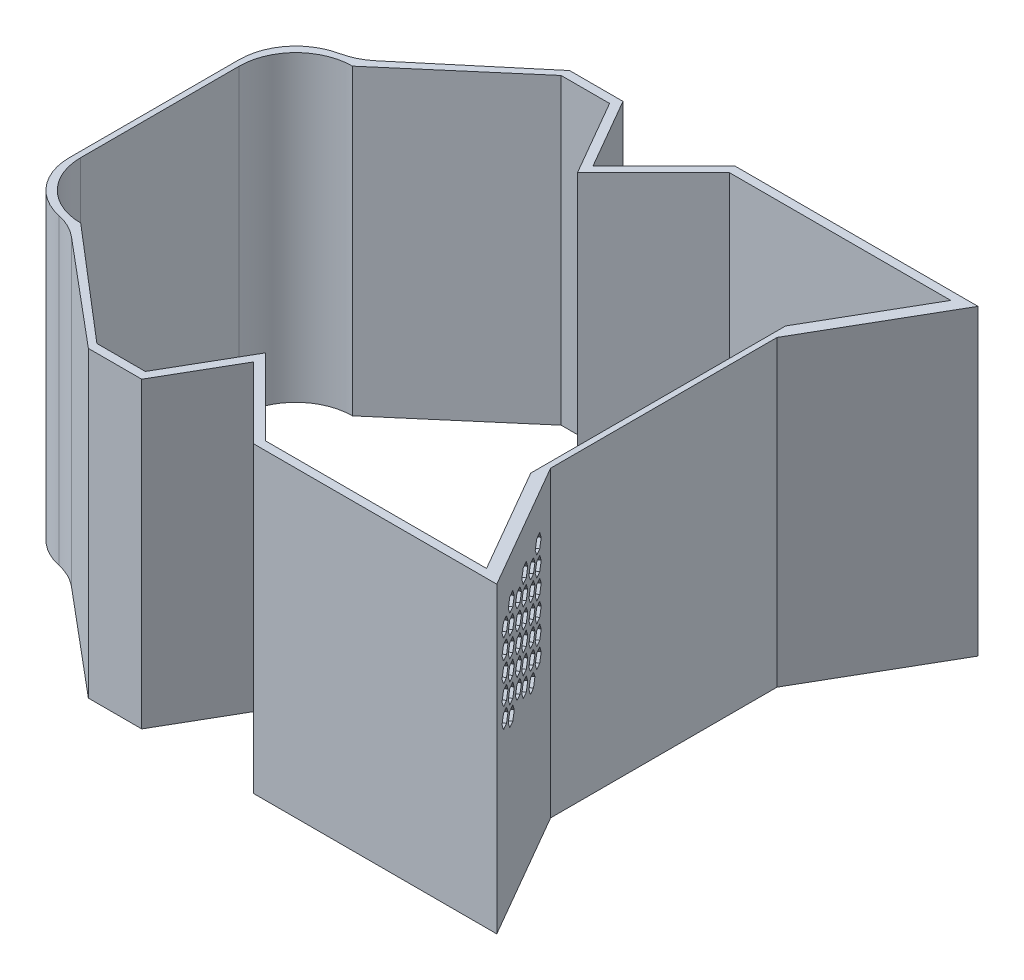
SolidWorks part; units mm, degrees
ref_plane "Ön Düzlem" through (0, 0, 0) normal (0, 0, 1) x (1, 0, 0)
ref_plane "Üst Düzlem" through (0, 0, 0) normal (0, 1, 0) x (1, 0, 0)
ref_plane "Sağ Düzlem" through (0, 0, 0) normal (1, 0, 0) x (0, 0, -1)
sketch "Çizim1" plane through (0, 0, 0) normal (0, 1, 0) x (1, 0, 0)
  line L2 (-90, -30) -> (-90, 30)
  line L4 (90, -40) -> (90, 40)
  line L6 (19.6213, -70.3787) -> (4.3568, -55.1141)
  line L8 (88, 0) -> (88, -38)
  line L9 (88, 38) -> (88, 0)
  line L14 (-88, 28) -> (-88, -28)
  line L22 (19.6213, -70.3787) -> (31.2426, -82)
  line L23 (5, -60) -> (30, -85)
  line L24 (-4.815, -71) -> (4.3568, -55.1141)
  line L25 (-28.2886, -85) -> (-9.4338, -85)
  line L26 (-65.4669, -53.8037) -> (-28.2886, -85)
  line L27 (5, -60) -> (-9.4338, -85)
  line L28 (30, -85) -> (115.9808, -85)
  line L29 (31.2426, -82) -> (109.362, -82)
  line L30 (90, -40) -> (115.9808, -85)
  line L31 (88, 45) -> (109.362, 82)
  line L32 (-68, -48) -> (-28.2886, -82)
  line L33 (-28.2886, -82) -> (-11.1658, -82)
  line L34 (-4.815, -71) -> (-11.1658, -82)
  line L35 (88, -38) -> (88, -45)
  line L36 (88, -45) -> (109.362, -82)
  line L37 (88, 38) -> (88, 45)
  line L38 (-4.815, 71) -> (-11.1658, 82)
  line L39 (-28.2886, 82) -> (-11.1658, 82)
  line L40 (-68, 48) -> (-28.2886, 82)
  line L41 (90, 40) -> (115.9808, 85)
  line L42 (31.2426, 82) -> (109.362, 82)
  line L43 (30, 85) -> (115.9808, 85)
  line L44 (5, 60) -> (-9.4338, 85)
  line L45 (-65.4669, 53.8037) -> (-28.2886, 85)
  line L46 (-28.2886, 85) -> (-9.4338, 85)
  line L47 (-4.815, 71) -> (4.3568, 55.1141)
  line L48 (5, 60) -> (30, 85)
  line L49 (19.6213, 70.3787) -> (31.2426, 82)
  line L50 (19.6213, 70.3787) -> (4.3568, 55.1141)
  arc A0 (-88, -28) -> (-68, -48) centre (-68, -28) ccw
  arc A2 (-74.1613, -49.5623) -> (-90, -30) centre (-70, -30) cw
  arc A8 (-65.4669, -53.8037) -> (-74.1613, -49.5623) centre (-78.3227, -69.1246) ccw
  arc A9 (-65.4669, 53.8037) -> (-74.1613, 49.5623) centre (-78.3227, 69.1246) cw
  arc A10 (-74.1613, 49.5623) -> (-90, 30) centre (-70, 30) ccw
  arc A11 (-88, 28) -> (-68, 48) centre (-68, 28) cw
  point P0 (0, 0)
  dimension "D1" = 20
extrude "Yükseklik-Ekstrüzyon1" add sketch "Çizim1" along normal blind 107
sketch "Çizim2" plane through (50.1795, 0, -28.9711) normal (0.866, 0, -0.5) x (-0.5, 0, -0.866)
  line L0 (-131.6025, 107) -> (-121.6025, 107)
  line L1 (-131.6025, 107) -> (-79.641, 107) construction
  line L2 (-121.6025, 107) -> (-111.6025, 107)
  line L3 (-111.6025, 107) -> (-101.6025, 107)
  line L4 (-101.6025, 107) -> (-91.6025, 107)
  line L5 (-91.6025, 107) -> (-81.6025, 107)
  line L7 (-90.1592, 80.5) -> (-88.7158, 78)
  line L10 (-90.1592, 24.5) -> (-88.7158, 22)
  line L13 (-88.7158, 36) -> (-90.1592, 38.5)
  line L15 (-88.7158, 92) -> (-90.1592, 94.5)
  line L16 (-90.1592, 94.5) -> (-93.0459, 94.5)
  line L17 (-93.0459, 94.5) -> (-94.4893, 92)
  line L18 (-94.4893, 92) -> (-93.0459, 89.5)
  line L19 (-93.0459, 89.5) -> (-90.1592, 89.5)
  line L20 (-90.1592, 89.5) -> (-88.7158, 92)
  line L30 (-88.7158, 85) -> (-90.1592, 87.5)
  line L31 (-90.1592, 87.5) -> (-93.0459, 87.5)
  line L32 (-93.0459, 87.5) -> (-94.4893, 85)
  line L33 (-94.4893, 85) -> (-93.0459, 82.5)
  line L34 (-93.0459, 82.5) -> (-90.1592, 82.5)
  line L35 (-90.1592, 82.5) -> (-88.7158, 85)
  line L36 (-103.1592, 80.5) -> (-101.7158, 78)
  line L37 (-103.1592, 24.5) -> (-101.7158, 22)
  line L38 (-93.0459, 80.5) -> (-90.1592, 80.5)
  line L39 (-94.4893, 78) -> (-93.0459, 80.5)
  line L40 (-93.0459, 75.5) -> (-94.4893, 78)
  line L41 (-90.1592, 75.5) -> (-93.0459, 75.5)
  line L42 (-88.7158, 78) -> (-90.1592, 75.5)
  line L50 (-90.1592, 73.5) -> (-88.7158, 71)
  line L51 (-93.0459, 73.5) -> (-90.1592, 73.5)
  line L52 (-94.4893, 71) -> (-93.0459, 73.5)
  line L53 (-93.0459, 68.5) -> (-94.4893, 71)
  line L54 (-90.1592, 68.5) -> (-93.0459, 68.5)
  line L55 (-88.7158, 71) -> (-90.1592, 68.5)
  line L61 (-88.7158, 64) -> (-90.1592, 66.5)
  line L62 (-90.1592, 66.5) -> (-93.0459, 66.5)
  line L63 (-93.0459, 66.5) -> (-94.4893, 64)
  line L64 (-94.4893, 64) -> (-93.0459, 61.5)
  line L65 (-93.0459, 61.5) -> (-90.1592, 61.5)
  line L66 (-90.1592, 61.5) -> (-88.7158, 64)
  line L73 (-88.7158, 57) -> (-90.1592, 59.5)
  line L74 (-90.1592, 59.5) -> (-93.0459, 59.5)
  line L75 (-93.0459, 59.5) -> (-94.4893, 57)
  line L76 (-94.4893, 57) -> (-93.0459, 54.5)
  line L77 (-93.0459, 54.5) -> (-90.1592, 54.5)
  line L78 (-90.1592, 52.5) -> (-88.7158, 50)
  line L79 (-93.0459, 52.5) -> (-90.1592, 52.5)
  line L80 (-94.4893, 50) -> (-93.0459, 52.5)
  line L81 (-93.0459, 47.5) -> (-94.4893, 50)
  line L82 (-90.1592, 47.5) -> (-93.0459, 47.5)
  line L83 (-88.7158, 50) -> (-90.1592, 47.5)
  line L91 (-90.1592, 45.5) -> (-88.7158, 43)
  line L92 (-93.0459, 45.5) -> (-90.1592, 45.5)
  line L93 (-94.4893, 43) -> (-93.0459, 45.5)
  line L94 (-93.0459, 40.5) -> (-94.4893, 43)
  line L95 (-90.1592, 40.5) -> (-93.0459, 40.5)
  line L96 (-88.7158, 43) -> (-90.1592, 40.5)
  line L99 (-90.1592, 54.5) -> (-88.7158, 57)
  line L100 (-90.1592, 38.5) -> (-93.0459, 38.5)
  line L101 (-93.0459, 38.5) -> (-94.4893, 36)
  line L102 (-94.4893, 36) -> (-93.0459, 33.5)
  line L103 (-93.0459, 33.5) -> (-90.1592, 33.5)
  line L104 (-90.1592, 33.5) -> (-88.7158, 36)
  line L111 (-88.7158, 29) -> (-90.1592, 31.5)
  line L112 (-90.1592, 31.5) -> (-93.0459, 31.5)
  line L113 (-93.0459, 31.5) -> (-94.4893, 29)
  line L114 (-94.4893, 29) -> (-93.0459, 26.5)
  line L115 (-93.0459, 26.5) -> (-90.1592, 26.5)
  line L116 (-90.1592, 26.5) -> (-88.7158, 29)
  line L117 (-93.0459, 24.5) -> (-90.1592, 24.5)
  line L118 (-94.4893, 22) -> (-93.0459, 24.5)
  line L119 (-93.0459, 19.5) -> (-94.4893, 22)
  line L120 (-90.1592, 19.5) -> (-93.0459, 19.5)
  line L121 (-88.7158, 22) -> (-90.1592, 19.5)
  line L126 (-101.7158, 36) -> (-103.1592, 38.5)
  line L127 (-101.7158, 92) -> (-103.1592, 94.5)
  line L129 (-103.1592, 94.5) -> (-106.0459, 94.5)
  line L130 (-94.7773, 88.4998) -> (-96.2207, 90.9998)
  line L136 (-96.2207, 90.9998) -> (-99.1075, 90.9998)
  line L137 (-99.1075, 90.9998) -> (-100.5508, 88.4998)
  line L138 (-100.5508, 88.4998) -> (-99.1075, 85.9998)
  line L139 (-99.1075, 85.9998) -> (-96.2207, 85.9998)
  line L140 (-96.2207, 85.9998) -> (-94.7773, 88.4998)
  line L141 (-96.2206, 84) -> (-94.7772, 81.5)
  line L142 (-99.1074, 84) -> (-96.2206, 84)
  line L143 (-100.5507, 81.5) -> (-99.1074, 84)
  line L144 (-99.1074, 79) -> (-100.5507, 81.5)
  line L145 (-96.2206, 79) -> (-99.1074, 79)
  line L151 (-94.7772, 81.5) -> (-96.2206, 79)
  line L153 (-106.0459, 94.5) -> (-107.4893, 92)
  line L155 (-107.4893, 92) -> (-106.0459, 89.5)
  line L156 (-106.0459, 89.5) -> (-103.1592, 89.5)
  line L159 (-94.7772, 74.5) -> (-96.2206, 77)
  line L165 (-96.2206, 77) -> (-99.1074, 77)
  line L166 (-99.1074, 77) -> (-100.5507, 74.5)
  line L167 (-100.5507, 74.5) -> (-99.1074, 72)
  line L168 (-99.1074, 72) -> (-96.2206, 72)
  line L169 (-96.2206, 72) -> (-94.7772, 74.5)
  line L170 (-96.2206, 70) -> (-94.7772, 67.5)
  line L171 (-99.1074, 70) -> (-96.2206, 70)
  line L172 (-100.5507, 67.5) -> (-99.1074, 70)
  line L173 (-99.1074, 65) -> (-100.5507, 67.5)
  line L174 (-96.2206, 65) -> (-99.1074, 65)
  line L180 (-94.7772, 67.5) -> (-96.2206, 65)
  line L181 (-103.1592, 89.5) -> (-101.7158, 92)
  line L183 (-101.7158, 85) -> (-103.1592, 87.5)
  line L186 (-103.1592, 87.5) -> (-106.0459, 87.5)
  line L189 (-106.0459, 87.5) -> (-107.4893, 85)
  line L190 (-107.4893, 85) -> (-106.0459, 82.5)
  line L191 (-106.0459, 82.5) -> (-103.1592, 82.5)
  line L192 (-103.1592, 82.5) -> (-101.7158, 85)
  line L193 (-106.0459, 80.5) -> (-103.1592, 80.5)
  line L195 (-94.7772, 60.5013) -> (-96.2206, 63.0013)
  line L197 (-107.4893, 78) -> (-106.0459, 80.5)
  line L198 (-106.0459, 75.5) -> (-107.4893, 78)
  line L199 (-103.1592, 75.5) -> (-106.0459, 75.5)
  line L200 (-96.2206, 63.0013) -> (-99.1074, 63.0013)
  line L201 (-99.1074, 63.0013) -> (-100.5507, 60.5013)
  line L202 (-100.5507, 60.5013) -> (-99.1074, 58.0013)
  line L203 (-99.1074, 58.0013) -> (-96.2206, 58.0013)
  line L204 (-96.2206, 58.0013) -> (-94.7772, 60.5013)
  line L205 (-96.2206, 56.0013) -> (-94.7772, 53.5013)
  line L206 (-99.1074, 56.0013) -> (-96.2206, 56.0013)
  line L207 (-100.5507, 53.5013) -> (-99.1074, 56.0013)
  line L208 (-99.1074, 51.0013) -> (-100.5507, 53.5013)
  line L209 (-96.2206, 51.0013) -> (-99.1074, 51.0013)
  line L215 (-94.7772, 53.5013) -> (-96.2206, 51.0013)
  line L219 (-101.7158, 78) -> (-103.1592, 75.5)
  line L220 (-103.1592, 73.5) -> (-101.7158, 71)
  line L221 (-106.0459, 73.5) -> (-103.1592, 73.5)
  line L223 (-94.7772, 46.5013) -> (-96.2206, 49.0013)
  line L229 (-96.2206, 49.0013) -> (-99.1074, 49.0013)
  line L230 (-99.1074, 49.0013) -> (-100.5507, 46.5013)
  line L231 (-100.5507, 46.5013) -> (-99.1074, 44.0013)
  line L232 (-99.1074, 44.0013) -> (-96.2206, 44.0013)
  line L233 (-96.2206, 44.0013) -> (-94.7772, 46.5013)
  line L234 (-96.2206, 42.0013) -> (-94.7772, 39.5013)
  line L235 (-99.1074, 42.0013) -> (-96.2206, 42.0013)
  line L236 (-100.5507, 39.5013) -> (-99.1074, 42.0013)
  line L237 (-99.1074, 37.0013) -> (-100.5507, 39.5013)
  line L238 (-96.2206, 37.0013) -> (-99.1074, 37.0013)
  line L244 (-94.7772, 39.5013) -> (-96.2206, 37.0013)
  line L245 (-107.4893, 71) -> (-106.0459, 73.5)
  line L248 (-106.0459, 68.5) -> (-107.4893, 71)
  line L252 (-103.1592, 68.5) -> (-106.0459, 68.5)
  line L254 (-101.7158, 71) -> (-103.1592, 68.5)
  line L257 (-101.7158, 64) -> (-103.1592, 66.5)
  line L260 (-103.1592, 66.5) -> (-106.0459, 66.5)
  line L265 (-106.0459, 66.5) -> (-107.4893, 64)
  line L266 (-94.7772, 32.5013) -> (-96.2206, 35.0013)
  line L272 (-96.2206, 35.0013) -> (-99.1074, 35.0013)
  line L273 (-99.1074, 35.0013) -> (-100.5507, 32.5013)
  line L274 (-100.5507, 32.5013) -> (-99.1074, 30.0013)
  line L275 (-99.1074, 30.0013) -> (-96.2206, 30.0013)
  line L276 (-96.2206, 30.0013) -> (-94.7772, 32.5013)
  line L277 (-96.2206, 28.0013) -> (-94.7772, 25.5013)
  line L278 (-99.1074, 28.0013) -> (-96.2206, 28.0013)
  line L279 (-100.5507, 25.5013) -> (-99.1074, 28.0013)
  line L280 (-99.1074, 23.0013) -> (-100.5507, 25.5013)
  line L281 (-96.2206, 23.0013) -> (-99.1074, 23.0013)
  line L287 (-94.7772, 25.5013) -> (-96.2206, 23.0013)
  line L289 (-107.4893, 64) -> (-106.0459, 61.5)
  line L291 (-106.0459, 61.5) -> (-103.1592, 61.5)
  line L292 (-103.1592, 61.5) -> (-101.7158, 64)
  line L295 (-94.7772, 18.5013) -> (-96.2206, 21.0013)
  line L301 (-96.2206, 21.0013) -> (-99.1074, 21.0013)
  line L302 (-99.1074, 21.0013) -> (-100.5507, 18.5013)
  line L303 (-100.5507, 18.5013) -> (-99.1074, 16.0013)
  line L304 (-99.1074, 16.0013) -> (-96.2206, 16.0013)
  line L305 (-96.2206, 16.0013) -> (-94.7772, 18.5013)
  line L316 (-101.7158, 57) -> (-103.1592, 59.5)
  line L323 (-103.1592, 59.5) -> (-106.0459, 59.5)
  line L325 (-106.0459, 59.5) -> (-107.4893, 57)
  line L326 (-94.4893, 36.0025) -> (-93.0459, 38.5025)
  line L327 (-93.0459, 33.5025) -> (-94.4893, 36.0025)
  line L328 (-107.4893, 57) -> (-106.0459, 54.5)
  line L329 (-93.0459, 31.5025) -> (-94.4893, 29.0025)
  line L330 (-94.4893, 29.0025) -> (-93.0459, 26.5025)
  line L331 (-106.0459, 54.5) -> (-103.1592, 54.5)
  line L332 (-103.1592, 52.5) -> (-101.7158, 50)
  line L333 (-106.0459, 52.5) -> (-103.1592, 52.5)
  line L334 (-93.0459, 24.5025) -> (-94.4893, 22.0025)
  line L335 (-94.4893, 22.0025) -> (-93.0459, 19.5025)
  line L337 (-107.4893, 50) -> (-106.0459, 52.5)
  line L338 (-106.0459, 47.5) -> (-107.4893, 50)
  line L341 (-103.1592, 47.5) -> (-106.0459, 47.5)
  line L342 (-101.7158, 50) -> (-103.1592, 47.5)
  line L345 (-103.1592, 45.5) -> (-101.7158, 43)
  line L346 (-106.0459, 45.5) -> (-103.1592, 45.5)
  line L347 (-107.4893, 43) -> (-106.0459, 45.5)
  line L350 (-106.0459, 40.5) -> (-107.4893, 43)
  line L357 (-103.1592, 40.5) -> (-106.0459, 40.5)
  line L358 (-101.7158, 43) -> (-103.1592, 40.5)
  line L359 (-103.1592, 54.5) -> (-101.7158, 57)
  line L360 (-103.1592, 38.5) -> (-106.0459, 38.5)
  line L361 (-106.0459, 38.5) -> (-107.4893, 36)
  line L362 (-107.4893, 36) -> (-106.0459, 33.5)
  line L363 (-106.0459, 33.5) -> (-103.1592, 33.5)
  line L364 (-103.1592, 33.5) -> (-101.7158, 36)
  line L365 (-101.7158, 29) -> (-103.1592, 31.5)
  line L366 (-103.1592, 31.5) -> (-106.0459, 31.5)
  line L367 (-106.0459, 31.5) -> (-107.4893, 29)
  line L368 (-107.4893, 29) -> (-106.0459, 26.5)
  line L369 (-106.0459, 26.5) -> (-103.1592, 26.5)
  line L370 (-103.1592, 26.5) -> (-101.7158, 29)
  line L371 (-106.0459, 24.5) -> (-103.1592, 24.5)
  line L372 (-107.4893, 22) -> (-106.0459, 24.5)
  line L373 (-106.0459, 19.5) -> (-107.4893, 22)
  line L374 (-103.1592, 19.5) -> (-106.0459, 19.5)
  line L375 (-101.7158, 22) -> (-103.1592, 19.5)
  line L376 (-107.7773, 88.4998) -> (-109.2207, 90.9998)
  line L377 (-109.2207, 90.9998) -> (-112.1075, 90.9998)
  line L378 (-112.1075, 90.9998) -> (-113.5508, 88.4998)
  line L379 (-113.5508, 88.4998) -> (-112.1075, 85.9998)
  line L380 (-112.1075, 85.9998) -> (-109.2207, 85.9998)
  line L381 (-109.2207, 85.9998) -> (-107.7773, 88.4998)
  line L382 (-109.2206, 84) -> (-107.7772, 81.5)
  line L383 (-112.1074, 84) -> (-109.2206, 84)
  line L384 (-113.5507, 81.5) -> (-112.1074, 84)
  line L385 (-112.1074, 79) -> (-113.5507, 81.5)
  line L386 (-109.2206, 79) -> (-112.1074, 79)
  line L387 (-107.7772, 81.5) -> (-109.2206, 79)
  line L388 (-107.7772, 74.5) -> (-109.2206, 77)
  line L389 (-109.2206, 77) -> (-112.1074, 77)
  line L390 (-112.1074, 77) -> (-113.5507, 74.5)
  line L391 (-113.5507, 74.5) -> (-112.1074, 72)
  line L392 (-112.1074, 72) -> (-109.2206, 72)
  line L393 (-109.2206, 72) -> (-107.7772, 74.5)
  line L394 (-109.2206, 70) -> (-107.7772, 67.5)
  line L395 (-112.1074, 70) -> (-109.2206, 70)
  line L396 (-113.5507, 67.5) -> (-112.1074, 70)
  line L397 (-112.1074, 65) -> (-113.5507, 67.5)
  line L398 (-109.2206, 65) -> (-112.1074, 65)
  line L399 (-107.7772, 67.5) -> (-109.2206, 65)
  line L400 (-107.7772, 60.5013) -> (-109.2206, 63.0013)
  line L401 (-109.2206, 63.0013) -> (-112.1074, 63.0013)
  line L402 (-112.1074, 63.0013) -> (-113.5507, 60.5013)
  line L403 (-113.5507, 60.5013) -> (-112.1074, 58.0013)
  line L404 (-112.1074, 58.0013) -> (-109.2206, 58.0013)
  line L405 (-109.2206, 58.0013) -> (-107.7772, 60.5013)
  line L406 (-109.2206, 56.0013) -> (-107.7772, 53.5013)
  line L407 (-112.1074, 56.0013) -> (-109.2206, 56.0013)
  line L408 (-113.5507, 53.5013) -> (-112.1074, 56.0013)
  line L409 (-112.1074, 51.0013) -> (-113.5507, 53.5013)
  line L410 (-109.2206, 51.0013) -> (-112.1074, 51.0013)
  line L411 (-107.7772, 53.5013) -> (-109.2206, 51.0013)
  line L412 (-107.7772, 46.5013) -> (-109.2206, 49.0013)
  line L413 (-109.2206, 49.0013) -> (-112.1074, 49.0013)
  line L414 (-112.1074, 49.0013) -> (-113.5507, 46.5013)
  line L415 (-113.5507, 46.5013) -> (-112.1074, 44.0013)
  line L416 (-112.1074, 44.0013) -> (-109.2206, 44.0013)
  line L417 (-109.2206, 44.0013) -> (-107.7772, 46.5013)
  line L418 (-109.2206, 42.0013) -> (-107.7772, 39.5013)
  line L419 (-112.1074, 42.0013) -> (-109.2206, 42.0013)
  line L420 (-113.5507, 39.5013) -> (-112.1074, 42.0013)
  line L421 (-112.1074, 37.0013) -> (-113.5507, 39.5013)
  line L422 (-109.2206, 37.0013) -> (-112.1074, 37.0013)
  line L423 (-107.7772, 39.5013) -> (-109.2206, 37.0013)
  line L424 (-107.7772, 32.5013) -> (-109.2206, 35.0013)
  line L425 (-109.2206, 35.0013) -> (-112.1074, 35.0013)
  line L426 (-112.1074, 35.0013) -> (-113.5507, 32.5013)
  line L427 (-113.5507, 32.5013) -> (-112.1074, 30.0013)
  line L428 (-112.1074, 30.0013) -> (-109.2206, 30.0013)
  line L429 (-109.2206, 30.0013) -> (-107.7772, 32.5013)
  line L430 (-109.2206, 28.0013) -> (-107.7772, 25.5013)
  line L431 (-112.1074, 28.0013) -> (-109.2206, 28.0013)
  line L432 (-113.5507, 25.5013) -> (-112.1074, 28.0013)
  line L433 (-112.1074, 23.0013) -> (-113.5507, 25.5013)
  line L434 (-109.2206, 23.0013) -> (-112.1074, 23.0013)
  line L435 (-107.7772, 25.5013) -> (-109.2206, 23.0013)
  line L436 (-107.7772, 18.5013) -> (-109.2206, 21.0013)
  line L437 (-109.2206, 21.0013) -> (-112.1074, 21.0013)
  line L438 (-112.1074, 21.0013) -> (-113.5507, 18.5013)
  line L439 (-113.5507, 18.5013) -> (-112.1074, 16.0013)
  line L440 (-112.1074, 16.0013) -> (-109.2206, 16.0013)
  line L441 (-109.2206, 16.0013) -> (-107.7772, 18.5013)
  line L442 (-107.4893, 36.0025) -> (-106.0459, 38.5025)
  line L443 (-106.0459, 33.5025) -> (-107.4893, 36.0025)
  line L444 (-106.0459, 31.5025) -> (-107.4893, 29.0025)
  line L445 (-107.4893, 29.0025) -> (-106.0459, 26.5025)
  line L446 (-106.0459, 24.5025) -> (-107.4893, 22.0025)
  line L447 (-107.4893, 22.0025) -> (-106.0459, 19.5025)
  line L448 (-116.1592, 80.5) -> (-114.7158, 78)
  line L449 (-116.1592, 24.5) -> (-114.7158, 22)
  line L450 (-114.7158, 36) -> (-116.1592, 38.5)
  line L451 (-114.7158, 92) -> (-116.1592, 94.5)
  line L452 (-116.1592, 94.5) -> (-119.0459, 94.5)
  line L453 (-119.0459, 94.5) -> (-120.4893, 92)
  line L454 (-120.4893, 92) -> (-119.0459, 89.5)
  line L455 (-119.0459, 89.5) -> (-116.1592, 89.5)
  line L456 (-116.1592, 89.5) -> (-114.7158, 92)
  line L457 (-114.7158, 85) -> (-116.1592, 87.5)
  line L458 (-116.1592, 87.5) -> (-119.0459, 87.5)
  line L459 (-119.0459, 87.5) -> (-120.4893, 85)
  line L460 (-120.4893, 85) -> (-119.0459, 82.5)
  line L461 (-119.0459, 82.5) -> (-116.1592, 82.5)
  line L462 (-116.1592, 82.5) -> (-114.7158, 85)
  line L463 (-119.0459, 80.5) -> (-116.1592, 80.5)
  line L464 (-120.4893, 78) -> (-119.0459, 80.5)
  line L465 (-119.0459, 75.5) -> (-120.4893, 78)
  line L466 (-116.1592, 75.5) -> (-119.0459, 75.5)
  line L467 (-114.7158, 78) -> (-116.1592, 75.5)
  line L468 (-116.1592, 73.5) -> (-114.7158, 71)
  line L469 (-119.0459, 73.5) -> (-116.1592, 73.5)
  line L470 (-120.4893, 71) -> (-119.0459, 73.5)
  line L471 (-119.0459, 68.5) -> (-120.4893, 71)
  line L472 (-116.1592, 68.5) -> (-119.0459, 68.5)
  line L473 (-114.7158, 71) -> (-116.1592, 68.5)
  line L474 (-114.7158, 64) -> (-116.1592, 66.5)
  line L475 (-116.1592, 66.5) -> (-119.0459, 66.5)
  line L476 (-119.0459, 66.5) -> (-120.4893, 64)
  line L477 (-120.4893, 64) -> (-119.0459, 61.5)
  line L478 (-119.0459, 61.5) -> (-116.1592, 61.5)
  line L479 (-116.1592, 61.5) -> (-114.7158, 64)
  line L480 (-114.7158, 57) -> (-116.1592, 59.5)
  line L481 (-116.1592, 59.5) -> (-119.0459, 59.5)
  line L482 (-119.0459, 59.5) -> (-120.4893, 57)
  line L483 (-120.4893, 57) -> (-119.0459, 54.5)
  line L484 (-119.0459, 54.5) -> (-116.1592, 54.5)
  line L485 (-116.1592, 52.5) -> (-114.7158, 50)
  line L486 (-119.0459, 52.5) -> (-116.1592, 52.5)
  line L487 (-120.4893, 50) -> (-119.0459, 52.5)
  line L488 (-119.0459, 47.5) -> (-120.4893, 50)
  line L489 (-116.1592, 47.5) -> (-119.0459, 47.5)
  line L490 (-114.7158, 50) -> (-116.1592, 47.5)
  line L491 (-116.1592, 45.5) -> (-114.7158, 43)
  line L492 (-119.0459, 45.5) -> (-116.1592, 45.5)
  line L493 (-120.4893, 43) -> (-119.0459, 45.5)
  line L494 (-119.0459, 40.5) -> (-120.4893, 43)
  line L495 (-116.1592, 40.5) -> (-119.0459, 40.5)
  line L496 (-114.7158, 43) -> (-116.1592, 40.5)
  line L497 (-116.1592, 54.5) -> (-114.7158, 57)
  line L498 (-116.1592, 38.5) -> (-119.0459, 38.5)
  line L499 (-119.0459, 38.5) -> (-120.4893, 36)
  line L500 (-120.4893, 36) -> (-119.0459, 33.5)
  line L501 (-119.0459, 33.5) -> (-116.1592, 33.5)
  line L502 (-116.1592, 33.5) -> (-114.7158, 36)
  line L503 (-114.7158, 29) -> (-116.1592, 31.5)
  line L504 (-116.1592, 31.5) -> (-119.0459, 31.5)
  line L505 (-119.0459, 31.5) -> (-120.4893, 29)
  line L506 (-120.4893, 29) -> (-119.0459, 26.5)
  line L507 (-119.0459, 26.5) -> (-116.1592, 26.5)
  line L508 (-116.1592, 26.5) -> (-114.7158, 29)
  line L509 (-119.0459, 24.5) -> (-116.1592, 24.5)
  line L510 (-120.4893, 22) -> (-119.0459, 24.5)
  line L511 (-119.0459, 19.5) -> (-120.4893, 22)
  line L512 (-116.1592, 19.5) -> (-119.0459, 19.5)
  line L513 (-114.7158, 22) -> (-116.1592, 19.5)
  line L514 (-120.7773, 88.4998) -> (-122.2207, 90.9998)
  line L515 (-122.2207, 90.9998) -> (-125.1075, 90.9998)
  line L516 (-125.1075, 90.9998) -> (-126.5508, 88.4998)
  line L517 (-126.5508, 88.4998) -> (-125.1075, 85.9998)
  line L518 (-125.1075, 85.9998) -> (-122.2207, 85.9998)
  line L519 (-122.2207, 85.9998) -> (-120.7773, 88.4998)
  line L520 (-122.2206, 84) -> (-120.7772, 81.5)
  line L521 (-125.1074, 84) -> (-122.2206, 84)
  line L522 (-126.5507, 81.5) -> (-125.1074, 84)
  line L523 (-125.1074, 79) -> (-126.5507, 81.5)
  line L524 (-122.2206, 79) -> (-125.1074, 79)
  line L525 (-120.7772, 81.5) -> (-122.2206, 79)
  line L526 (-120.7772, 74.5) -> (-122.2206, 77)
  line L527 (-122.2206, 77) -> (-125.1074, 77)
  line L528 (-125.1074, 77) -> (-126.5507, 74.5)
  line L529 (-126.5507, 74.5) -> (-125.1074, 72)
  line L530 (-125.1074, 72) -> (-122.2206, 72)
  line L531 (-122.2206, 72) -> (-120.7772, 74.5)
  line L532 (-122.2206, 70) -> (-120.7772, 67.5)
  line L533 (-125.1074, 70) -> (-122.2206, 70)
  line L534 (-126.5507, 67.5) -> (-125.1074, 70)
  line L535 (-125.1074, 65) -> (-126.5507, 67.5)
  line L536 (-122.2206, 65) -> (-125.1074, 65)
  line L537 (-120.7772, 67.5) -> (-122.2206, 65)
  line L538 (-120.7772, 60.5013) -> (-122.2206, 63.0013)
  line L539 (-122.2206, 63.0013) -> (-125.1074, 63.0013)
  line L540 (-125.1074, 63.0013) -> (-126.5507, 60.5013)
  line L541 (-126.5507, 60.5013) -> (-125.1074, 58.0013)
  line L542 (-125.1074, 58.0013) -> (-122.2206, 58.0013)
  line L543 (-122.2206, 58.0013) -> (-120.7772, 60.5013)
  line L544 (-122.2206, 56.0013) -> (-120.7772, 53.5013)
  line L545 (-125.1074, 56.0013) -> (-122.2206, 56.0013)
  line L546 (-126.5507, 53.5013) -> (-125.1074, 56.0013)
  line L547 (-125.1074, 51.0013) -> (-126.5507, 53.5013)
  line L548 (-122.2206, 51.0013) -> (-125.1074, 51.0013)
  line L549 (-120.7772, 53.5013) -> (-122.2206, 51.0013)
  line L550 (-120.7772, 46.5013) -> (-122.2206, 49.0013)
  line L551 (-122.2206, 49.0013) -> (-125.1074, 49.0013)
  line L552 (-125.1074, 49.0013) -> (-126.5507, 46.5013)
  line L553 (-126.5507, 46.5013) -> (-125.1074, 44.0013)
  line L554 (-125.1074, 44.0013) -> (-122.2206, 44.0013)
  line L555 (-122.2206, 44.0013) -> (-120.7772, 46.5013)
  line L556 (-122.2206, 42.0013) -> (-120.7772, 39.5013)
  line L557 (-125.1074, 42.0013) -> (-122.2206, 42.0013)
  line L558 (-126.5507, 39.5013) -> (-125.1074, 42.0013)
  line L559 (-125.1074, 37.0013) -> (-126.5507, 39.5013)
  line L560 (-122.2206, 37.0013) -> (-125.1074, 37.0013)
  line L561 (-120.7772, 39.5013) -> (-122.2206, 37.0013)
  line L562 (-120.7772, 32.5013) -> (-122.2206, 35.0013)
  line L563 (-122.2206, 35.0013) -> (-125.1074, 35.0013)
  line L564 (-125.1074, 35.0013) -> (-126.5507, 32.5013)
  line L565 (-126.5507, 32.5013) -> (-125.1074, 30.0013)
  line L566 (-125.1074, 30.0013) -> (-122.2206, 30.0013)
  line L567 (-122.2206, 30.0013) -> (-120.7772, 32.5013)
  line L568 (-122.2206, 28.0013) -> (-120.7772, 25.5013)
  line L569 (-125.1074, 28.0013) -> (-122.2206, 28.0013)
  line L570 (-126.5507, 25.5013) -> (-125.1074, 28.0013)
  line L571 (-125.1074, 23.0013) -> (-126.5507, 25.5013)
  line L572 (-122.2206, 23.0013) -> (-125.1074, 23.0013)
  line L573 (-120.7772, 25.5013) -> (-122.2206, 23.0013)
  line L574 (-120.7772, 18.5013) -> (-122.2206, 21.0013)
  line L575 (-122.2206, 21.0013) -> (-125.1074, 21.0013)
  line L576 (-125.1074, 21.0013) -> (-126.5507, 18.5013)
  line L577 (-126.5507, 18.5013) -> (-125.1074, 16.0013)
  line L578 (-125.1074, 16.0013) -> (-122.2206, 16.0013)
  line L579 (-122.2206, 16.0013) -> (-120.7772, 18.5013)
  line L580 (-120.4893, 36.0025) -> (-119.0459, 38.5025)
  line L581 (-119.0459, 33.5025) -> (-120.4893, 36.0025)
  line L582 (-119.0459, 31.5025) -> (-120.4893, 29.0025)
  line L583 (-120.4893, 29.0025) -> (-119.0459, 26.5025)
  line L584 (-119.0459, 24.5025) -> (-120.4893, 22.0025)
  line L585 (-120.4893, 22.0025) -> (-119.0459, 19.5025)
  circle A0 centre (-91.6025, 92) radius 2.5 construction
  circle A1 centre (-104.6025, 92) radius 2.5 construction
  circle A2 centre (-104.6025, 85) radius 2.5 construction
  circle A3 centre (-91.6025, 85) radius 2.5 construction
  circle A4 centre (-91.6025, 78) radius 2.5 construction
  circle A5 centre (-104.6025, 78) radius 2.5 construction
  circle A6 centre (-104.6025, 71) radius 2.5 construction
  circle A7 centre (-91.6025, 71) radius 2.5 construction
  circle A8 centre (-104.6025, 64) radius 2.5 construction
  circle A9 centre (-104.6025, 57) radius 2.5 construction
  circle A10 centre (-104.6025, 50) radius 2.5 construction
  circle A11 centre (-104.6025, 43) radius 2.5 construction
  circle A12 centre (-91.6025, 64) radius 2.5 construction
  circle A13 centre (-104.6025, 36) radius 2.5 construction
  circle A14 centre (-104.6025, 29) radius 2.5 construction
  circle A15 centre (-91.6025, 57) radius 2.5 construction
  circle A16 centre (-91.6025, 50) radius 2.5 construction
  circle A17 centre (-104.6025, 22) radius 2.5 construction
  circle A18 centre (-110.6641, 88.4998) radius 2.5 construction
  circle A19 centre (-91.6025, 43) radius 2.5 construction
  circle A20 centre (-110.664, 81.5) radius 2.5 construction
  circle A21 centre (-110.664, 74.5) radius 2.5 construction
  circle A22 centre (-91.6025, 36) radius 2.5 construction
  circle A23 centre (-110.664, 67.5) radius 2.5 construction
  circle A24 centre (-110.664, 60.5013) radius 2.5 construction
  circle A25 centre (-91.6025, 29) radius 2.5 construction
  circle A26 centre (-91.6025, 22) radius 2.5 construction
  circle A27 centre (-110.6639, 53.5013) radius 2.5 construction
  circle A28 centre (-110.664, 46.5013) radius 2.5 construction
  circle A29 centre (-110.664, 39.5013) radius 2.5 construction
  circle A30 centre (-110.664, 32.5013) radius 2.5 construction
  circle A31 centre (-110.664, 25.5013) radius 2.5 construction
  circle A32 centre (-110.664, 18.5013) radius 2.5 construction
  circle A33 centre (-97.6641, 88.4998) radius 2.5 construction
  circle A34 centre (-97.664, 81.5) radius 2.5 construction
  circle A35 centre (-117.6025, 92) radius 2.5 construction
  circle A36 centre (-117.6025, 85) radius 2.5 construction
  circle A37 centre (-97.664, 74.5) radius 2.5 construction
  circle A38 centre (-97.664, 67.5) radius 2.5 construction
  circle A39 centre (-117.6025, 78) radius 2.5 construction
  circle A40 centre (-117.6025, 71) radius 2.5 construction
  circle A41 centre (-117.6025, 64) radius 2.5 construction
  circle A42 centre (-117.6025, 57) radius 2.5 construction
  circle A43 centre (-97.664, 60.5013) radius 2.5 construction
  circle A44 centre (-97.6639, 53.5013) radius 2.5 construction
  circle A45 centre (-117.6025, 50) radius 2.5 construction
  circle A46 centre (-117.6025, 43) radius 2.5 construction
  circle A47 centre (-97.664, 46.5013) radius 2.5 construction
  circle A48 centre (-97.664, 39.5013) radius 2.5 construction
  circle A49 centre (-117.6025, 36) radius 2.5 construction
  circle A50 centre (-117.6025, 29) radius 2.5 construction
  circle A51 centre (-117.6025, 22) radius 2.5 construction
  circle A52 centre (-123.6641, 88.4998) radius 2.5 construction
  circle A53 centre (-123.664, 81.5) radius 2.5 construction
  circle A54 centre (-123.664, 74.5) radius 2.5 construction
  circle A55 centre (-123.664, 67.5) radius 2.5 construction
  circle A56 centre (-123.664, 60.5013) radius 2.5 construction
  circle A57 centre (-97.664, 32.5013) radius 2.5 construction
  circle A58 centre (-97.664, 25.5013) radius 2.5 construction
  circle A59 centre (-123.6639, 53.5013) radius 2.5 construction
  circle A60 centre (-123.664, 46.5013) radius 2.5 construction
  circle A61 centre (-97.664, 18.5013) radius 2.5 construction
  circle A62 centre (-123.664, 39.5013) radius 2.5 construction
  circle A63 centre (-123.664, 32.5013) radius 2.5 construction
  circle A64 centre (-123.664, 25.5013) radius 2.5 construction
  circle A65 centre (-123.664, 18.5013) radius 2.5 construction
  point P8 (0, 0)
  point P565 (0, 0)
  point P566 (0, 0)
  dimension "D1" = 3
sketch "Çizim3" plane through (90, 0, 0) normal (1, 0, 0) x (0, 0, -1)
  line L0 (0, 107) -> (0, 89.414)
  line L1 (-40, 107) -> (40, 107) construction
extrude "Kes-Ekstrüzyon1" cut sketch "Çizim2" against normal blind 4.3 contours L180 L170 L171 L172 L173 L174 | L55 L50 L51 L52 L53 L54 | L168 L169 L159 L165 L166 L167 | L42 L7 L38 L39 L40 L41 | L151 L141 L142 L143 L144 L145 | L34 L35 L30 L31 L32 L33 | L19 L20 L15 L16 L17 L18 | L139 L140 L130 L136 L137 L138 | L156 L181 L127 L129 L153 L155 | L191 L192 L183 L186 L189 L190 | L380 L381 L376 L377 L378 L379 | L387 L382 L383 L384 L385 L386 | L219 L36 L193 L197 L198 L199 | L467 L448 L463 L464 L465 L466 | L518 L519 L514 L515 L516 L517 | L461 L462 L457 L458 L459 L460 | L455 L456 L451 L452 L453 L454 | L525 L520 L521 L522 L523 L524 | L254 L220 L221 L245 L248 L252 | L203 L204 L195 L200 L201 L202 | L65 L66 L61 L62 L63 L64 | L526 L527 L528 L529 L530 L531 | L468 L473 L472 L471 L470 L469 | L393 L388 L389 L390 L391 L392 | L394 L399 L398 L397 L396 L395 | L257 L260 L265 L289 L291 L292 | L75 L76 L77 L99 L73 L74 | L205 L215 L209 L208 L207 L206 | L316 L323 L325 L328 L331 L359 | L479 L474 L475 L476 L477 L478 | L532 L537 L536 L535 L534 L533 | L543 L538 L539 L540 L541 L542 | L480 L481 L482 L483 L484 L497 | L402 L403 L404 L405 L400 L401
